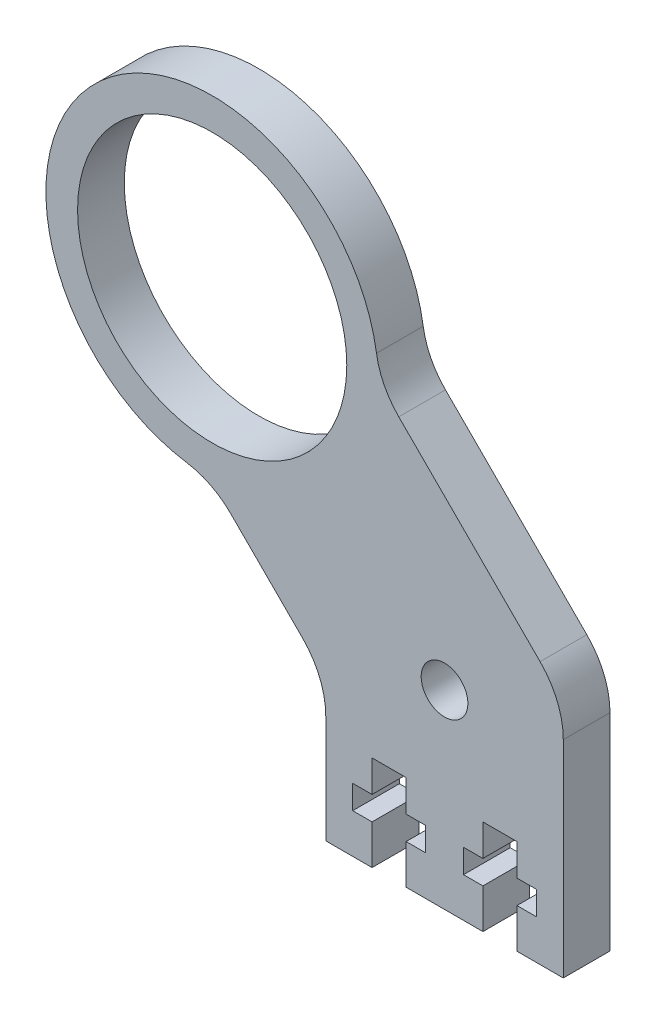
SolidWorks part; units mm, degrees
ref_plane "Front Plane" through (0, 0, 0) normal (0, 0, 1) x (1, 0, 0)
ref_plane "Top Plane" through (0, 0, 0) normal (0, 1, 0) x (1, 0, 0)
ref_plane "Right Plane" through (0, 0, 0) normal (1, 0, 0) x (0, 0, -1)
sketch "Sketch1" plane through (0, 0, 0) normal (0, 0, 1) x (1, 0, 0)
  line L0 (0, 0) -> (-29.3449, 29.3449) construction
  line L1 (0, 0) -> (0, 31.0325) construction
  line L2 (-15, -6.2132) -> (-15, -24)
  line L3 (-15, -24) -> (15, -24)
  line L4 (15, -24) -> (15, 6.2132)
  line L5 (0, 0) -> (0, -24) construction
  line L6 (15, 6.2132) -> (-8.346, 29.5592)
  line L7 (-15, -6.2132) -> (-29.5592, 8.346)
  line L8 (10.6066, 10.6066) -> (-18.7383, 39.9515) construction
  line L9 (-10.6066, -10.6066) -> (-39.9515, 18.7383) construction
  circle A0 centre (0, 0) radius 2.95
  arc A1 (-8.346, 29.5592) -> (-29.5592, 8.346) centre (-29.3449, 29.3449) ccw
  dimension "D1" = 5.9
  dimension "D3" = 42
  dimension "D2" = 41.5
  dimension "D4" = 45
  dimension "D5" = 24
  dimension "D6" = 30
  dimension "D7" = 15
  dimension "D8" = 15
extrude "Boss-Extrude1" add sketch "Sketch1" along normal blind 5.9
sketch "Sketch2" plane through (0, 0, 5.9) normal (0, 0, 1) x (1, 0, 0)
  circle A0 centre (-29.3449, 29.3449) radius 17
  dimension "D1" = 34
extrude "Cut-Extrude1" cut sketch "Sketch2" against normal through all
sketch "Sketch3" plane through (0, 0, 5.9) normal (0, 0, 1) x (1, 0, 0)
  line L0 (-15, -24) -> (15, -24) construction
  line L1 (-9.15, -24) -> (-4.85, -24)
  line L2 (-9.15, -24) -> (-9.15, -19)
  line L3 (-9.15, -12) -> (-4.85, -12)
  line L4 (-4.85, -24) -> (-4.85, -19)
  line L5 (0, 0) -> (0, -24) construction
  line L6 (-4.85, -16) -> (-2.4, -16)
  line L7 (-11.6, -16) -> (-9.15, -16)
  line L8 (-11.6, -16) -> (-11.6, -19)
  line L9 (-11.6, -19) -> (-9.15, -19)
  line L10 (-2.4, -16) -> (-2.4, -19)
  line L11 (-9.15, -16) -> (-9.15, -12)
  line L12 (-4.85, -19) -> (-2.4, -19)
  line L13 (-4.85, -16) -> (-4.85, -12)
  line L14 (4.85, -16) -> (4.85, -12)
  line L15 (4.85, -19) -> (2.4, -19)
  line L16 (9.15, -16) -> (9.15, -12)
  line L17 (2.4, -16) -> (2.4, -19)
  line L18 (11.6, -19) -> (9.15, -19)
  line L19 (11.6, -16) -> (11.6, -19)
  line L20 (11.6, -16) -> (9.15, -16)
  line L21 (4.85, -16) -> (2.4, -16)
  line L22 (4.85, -24) -> (4.85, -19)
  line L23 (9.15, -12) -> (4.85, -12)
  line L24 (9.15, -24) -> (9.15, -19)
  line L25 (9.15, -24) -> (4.85, -24)
  point P6 (-7, -12)
  point P18 (-10.375, -19)
  dimension "D1" = 4.3
  dimension "D2" = 7
  dimension "D3" = 12
  dimension "D4" = 9.2
  dimension "D5" = 3
  dimension "D6" = 5
extrude "Cut-Extrude2" cut sketch "Sketch3" against normal through all
fillet "Fillet1" radius 10 4 edges at (-15, -6.2132, 2.95) (15, 6.2132, 2.95) (-29.5592, 8.346, 2.95) (-8.346, 29.5592, 2.95)
equation "\"smallPulleyTeeth\"= 15"
equation "\"largePulleyTeeth\"= 40"
equation "\"eighthThick\"= 2.9mm"
equation "\"sixteenthThick\"= 1.7mm"
equation "\"quarterThick\"=5.9mm"
equation "\"OD\"= 145mm"
equation "\"puckAngle\"= 60.5deg"
equation "\"puckDiam\"= 76.5mm"
equation "\"axlePress\"= 5.9mm"
equation "\"D1@Sketch1\"=\"axlePress\""
equation "\"D1@Boss-Extrude1\"=\"quarterThick\""
equation "\"press\"= 0.2mm"
equation "\"wheelClear\"= 0.3mm"
equation "\"10-32clear\"= 4.5mm"
equation "\"D1@Sketch3\"=\"10-32clear\" - \"press\""
equation "\"6-32clear\"= 3.3mm"
equation "\"8-32clear\"= 4.0mm"
equation "\"wheelHeight\"= 24mm"
equation "\"D5@Sketch1\"=\"wheelHeight\""
